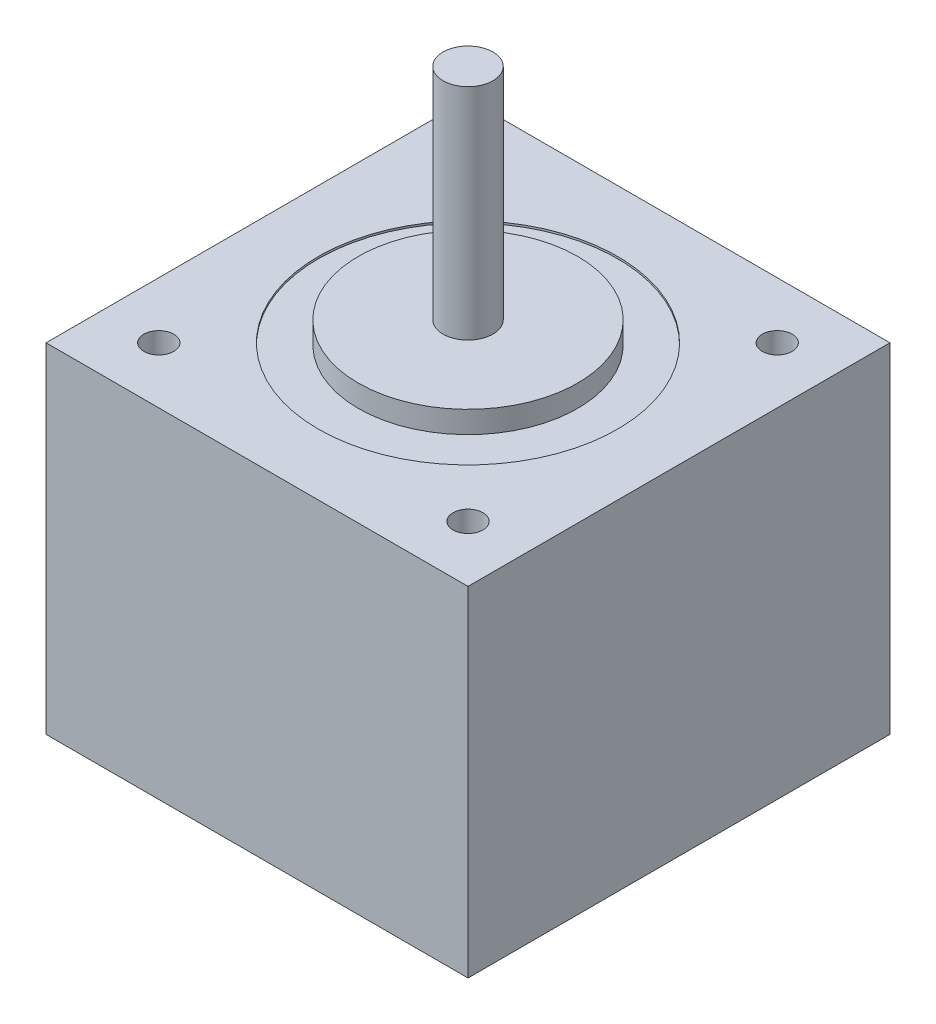
SolidWorks part; units mm, degrees
ref_plane "Front Plane" through (0, 0, 0) normal (0, 0, 1) x (1, 0, 0)
ref_plane "Top Plane" through (0, 0, 0) normal (0, 1, 0) x (1, 0, 0)
ref_plane "Right Plane" through (0, 0, 0) normal (1, 0, 0) x (0, 0, -1)
sketch "Sketch1" plane through (0, 0, 0) normal (0, 1, 0) x (1, 0, 0)
  line L1 (-21.15, 21.15) -> (21.15, 21.15)
  line L2 (-21.15, 21.15) -> (-21.15, -21.15)
  line L3 (-21.15, -21.15) -> (21.15, -21.15)
  line L4 (21.15, 21.15) -> (21.15, -21.15)
  line L5 (-21.15, 21.15) -> (21.15, -21.15) construction
  line L6 (-21.15, -21.15) -> (21.15, 21.15) construction
  point P0 (0, 0)
  dimension "D1" = 42.3
  dimension "D2" = 42.3
extrude "body" add sketch "Sketch1" along normal blind 34
sketch "Sketch2" plane through (0, 34, 0) normal (0, 1, 0) x (1, 0, 0)
  line L1 (-15.5, 15.5) -> (15.5, 15.5) construction
  line L2 (-15.5, 15.5) -> (-15.5, -15.5) construction
  line L3 (-15.5, -15.5) -> (15.5, -15.5) construction
  line L4 (15.5, 15.5) -> (15.5, -15.5) construction
  line L5 (-15.5, 15.5) -> (15.5, -15.5) construction
  line L6 (-15.5, -15.5) -> (15.5, 15.5) construction
  circle A0 centre (-15.5, 15.5) radius 1.5
  circle A1 centre (15.5, 15.5) radius 1.5
  circle A2 centre (15.5, -15.5) radius 1.5
  circle A3 centre (-15.5, -15.5) radius 1.5
  point P0 (0, 0)
  dimension "D3" = 3
  dimension "D4" = 3
  dimension "D5" = 3
  dimension "D6" = 3
  dimension "D1" = 31
  dimension "D2" = 31
extrude "mounting-holes" cut sketch "Sketch2" against normal blind 4
sketch "Sketch3" plane through (0, 34, 0) normal (0, 1, 0) x (1, 0, 0)
  circle A0 centre (0, 0) radius 11
  dimension "D1" = 22
extrude "center-thing" add sketch "Sketch3" along normal blind 2
sketch "Sketch4" plane through (0, 36, 0) normal (0, 1, 0) x (1, 0, 0)
  circle A0 centre (0, 0) radius 2.5
  dimension "D1" = 5
extrude "shaft" add sketch "Sketch4" along normal blind 22
sketch "Sketch5" plane through (0, 34, 0) normal (0, 1, 0) x (1, 0, 0)
  circle A0 centre (0, 0) radius 15
  circle A1 centre (0, 0) radius 11
  dimension "D1" = 30
extrude "large-divot" cut sketch "Sketch5" against normal blind 0.2 contours A0
